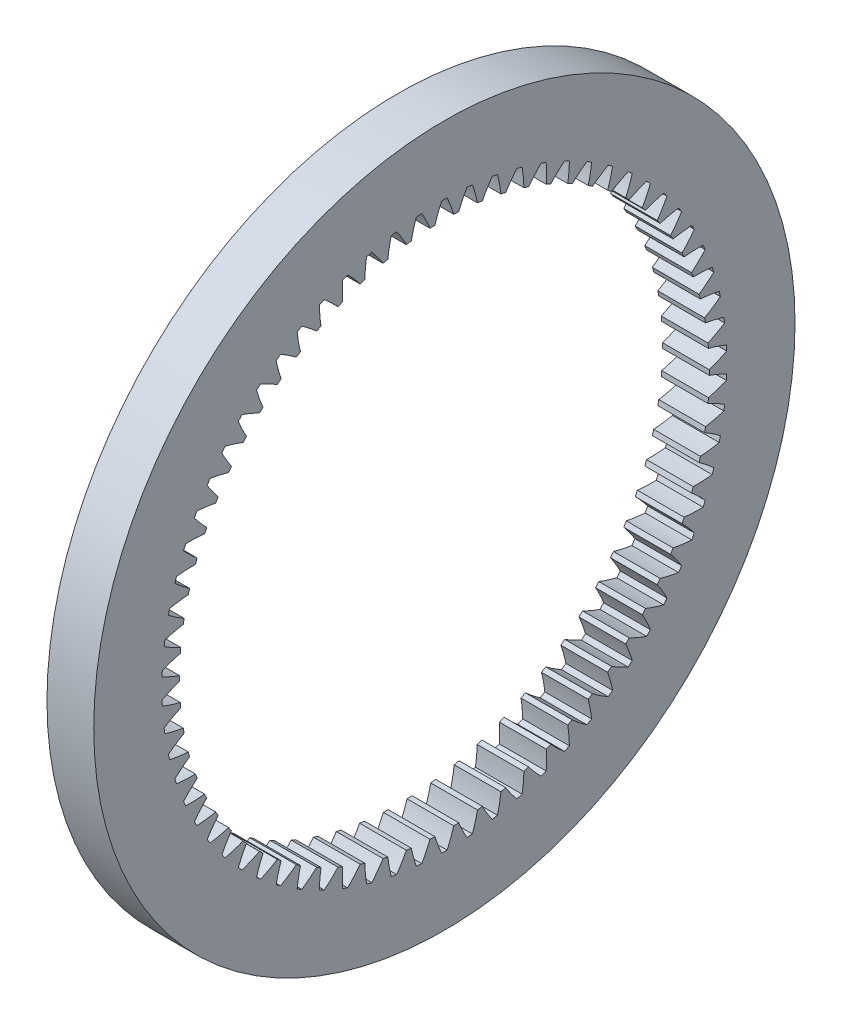
SolidWorks part; units mm, degrees
ref_plane "Plane1" through (0, 0, 0) normal (0, 0, 1) x (1, 0, 0)
ref_plane "Plane2" through (0, 0, 0) normal (0, 1, 0) x (1, 0, 0)
ref_plane "Plane3" through (0, 0, 0) normal (1, 0, 0) x (0, 0, -1)
sketch "HoldingSke" plane through (0, 0, 0) normal (0, 1, 0) x (1, 0, 0)
  line L0 (0, 0) -> (0.0684, -0.1879)
  line L1 (-15, 0) -> (100, 0) construction
  line L2 (0, 0) -> (-2.1039, 2.3779)
  line L3 (0, 0) -> (-11.863, 4.5341)
  line L4 (0, 0) -> (2.9537, 8.1152)
  line L5 (0, 0) -> (-23.7986, -8.8762)
  line L6 (0, 0) -> (-10.5278, -7.1032)
  line L7 (-2.1039, 2.3779) -> (3.3635, 27.1825)
  line L8 (-76.2, 7.3779) -> (-54.61, 7.3779)
  line L9 (-71.009, 38.7566) -> (-53.1078, 45.2721)
  line L10 (-76.2, 71.12) -> (104.1128, 71.12)
  line L11 (0, 0) -> (-30, 0)
  line L12 (-76.2, 101.6) -> (-76.033, 101.6)
  line L13 (24.9733, 27.94) -> (52.9518, 28.4284)
  line L14 (24.9733, 27.94) -> (24.9743, 27.94)
  line L15 (24.9733, 27.94) -> (100.4006, 29.5858)
  circle A0 centre (0, 0) radius 225
  circle A1 centre (0, 0) radius 12.7
  circle A2 centre (0, 0) radius 12.7
  dimension "MHD" = 25.4
  dimension "Hub_dia" = 25.4
  dimension "Diameter" = 450
  dimension "Num_teeth" = 70
  dimension "Pitch" = 0.2
  dimension "Overall_len" = 25.4
  dimension "Show_teeth" = 70
  dimension "Thickness" = 12.7
  dimension "OAL" = 25.4001
  dimension "T_dim" = 21.59
  dimension "Ap" = 20
  dimension "H" = 19.05
  dimension "Pitch_radius" = 180.3128
  dimension "Width" = 30
  dimension "Backlash" = 0.167
  dimension "Addendum_fac" = 1
  dimension "Dedendum_fac" = 1.25
  dimension "Clearance_fac" = 0.25
  dimension "Dedendum_add" = 0.001
  dimension "Module" = 5
sketch "BasProSke" plane through (0, 0, 0) normal (0, 1, 0) x (1, 0, 0)
  line L0 (-10, 0) -> (60, 0) construction
  line L1 (0, 170) -> (0, 225)
  line L2 (0, 170) -> (30, 170)
  line L3 (30, 170) -> (30, 225)
  line L4 (30, 225) -> (0, 225)
  dimension "Diameter" = 450
  dimension "Thickness" = 30
  dimension "Inside_diameter" = 340
revolve "Base-Revolve" add sketch "BasProSke" angle 360 about L0
sketch "TooCutSke" plane through (0, 0, 0) normal (1, 0, 0) x (0, 0, -1)
  line L3 (4.3442, 174.9461) -> (4.3442, 53.6633) construction
  line L4 (0, 0) -> (0, 59.563) construction
  line L5 (0, 0) -> (-3.0655, 68.2587) construction
  line L6 (-77.747, 144.6591) -> (31.1646, 149.5504) construction
  circle A0 centre (0, 0) radius 175 construction
  circle A1 centre (0, 0) radius 181.251 construction
  circle A2 centre (0, 0) radius 148.0016 construction
  circle A3 centre (0, 0) radius 169.9746 construction
  arc A4 (6.0433, 169.8671) -> (1.7382, 181.2427) centre (-77.747, 144.6591) ccw
  arc A5 (6.0433, 169.8671) -> (-6.0433, 169.8671) centre (0, 0) ccw
  arc A6 (1.7382, 181.2427) -> (-1.7382, 181.2427) centre (0, 0) ccw
  arc A7 (-1.7382, 181.2427) -> (-6.0433, 169.8671) centre (77.747, 144.6591) ccw
  dimension "Pitch_dia" = 350
  dimension "Base_dia" = 296.0032
  dimension "Root_dia" = 362.502
  dimension "Overcut_dia" = 339.9492
  dimension "Flank_rad" = 87.5
  dimension "Half_ang" = 2.571
  dimension "Half_CT" = 4.3442
extrude "ToothCut" cut sketch "TooCutSke" along normal through all
fillet "Breaks" [suppressed] radius 0.5
fillet "RootFillets" [suppressed] radius 1.251
pattern_circular "TeethCuts" count 70 every 5.143 about axis through (-10, 0, 0) along (1, 0, 0) of "RootFillets", "Breaks", "ToothCut"
equation "' \"Module@HoldingSke\" = 6.35"
equation "' \"Num_teeth@HoldingSke\" = 24"
equation "' \"Ap@HoldingSke\" =  14.5"
equation "' \"Ap@HoldingSke\" = 14.5"
equation "' \"Width@HoldingSke\" = 12"
equation "' \"Diameter@HoldingSke\" = 8 * 25.4"
equation "' \"Show_teeth@HoldingSke\" = 100"
equation "' \"Backlash@HoldingSke\" = 0.009 * 25.4"
equation "' \"Addendum_fac@HoldingSke\" = 1.0"
equation "' \"Dedendum_fac@HoldingSke\" = 1.25"
equation "' \"Dedendum_add@HoldingSke\" = 0.00005 * 25.4"
equation "' \"Clearance_fac@HoldingSke\" = 0.25"
equation "\"Pitch@HoldingSke\" = 1 / \"Module@HoldingSke\" "
equation "\"Overcut_dia@TooCutSke\" = (\"Num_teeth@HoldingSke\" - 2 * \"Addendum_fac@HoldingSke\") / \"Pitch@HoldingSke\" - 0.002 * 25.4"
equation "\"Pitch_dia@TooCutSke\" = \"Num_teeth@HoldingSke\" / \"Pitch@HoldingSke\""
equation "\"Base_dia@TooCutSke\" = \"Num_teeth@HoldingSke\" / \"Pitch@HoldingSke\" * cos((\"Ap@HoldingSke\"  * 3.14159265 / 180)) * 0.90"
equation "\"Root_dia@TooCutSke\" = \"Num_teeth@HoldingSke\"  / \"Pitch@HoldingSke\" + 2 *  \"Dedendum_fac@HoldingSke\"/ \"Pitch@HoldingSke\" + \"Dedendum_add@HoldingSke\" * 2"
equation "\"Half_ang@TooCutSke\" = 180 / \"Num_teeth@HoldingSke\""
equation "\"Half_CT@TooCutSke\" = \"Num_teeth@HoldingSke\" / \"Pitch@HoldingSke\" * sin((3.14159265 / 2 / \"Num_teeth@HoldingSke\")) / 2 + 10 * \"Backlash@HoldingSke\" / 4"
equation "\"Flank_rad@TooCutSke\" = \"Num_teeth@HoldingSke\" / \"Pitch@HoldingSke\" / 4"
equation "\"Radius@RootFillets\"= \"Clearance_fac@HoldingSke\" / \"Pitch@HoldingSke\" + \"Dedendum_add@HoldingSke\""
equation "\"Break_rad@Breaks\" = 0.02 / \"Pitch@HoldingSke\" * 5"
equation "\"Num_teeth@TeethCuts\" = int( \"Show_teeth@HoldingSke\" ) + 1"
equation "\"Num_teeth@TeethCuts\" = ((sgn( \"Num_teeth@TeethCuts\" - \"Num_teeth@HoldingSke\" )-1)*( \"Num_teeth@TeethCuts\" - \"Num_teeth@HoldingSke\" ))/-2+ \"Num_teeth@HoldingSke\""
equation "\"Num_teeth@TeethCuts\" = ((sgn( \"Num_teeth@TeethCuts\" - 2.0)+1)*( \"Num_teeth@TeethCuts\" - 2.0))/2 +2.0"
equation "\"Angle@TeethCuts\" = 360.0 / \"Num_teeth@HoldingSke\""
equation "\"Diameter@BasProSke\" = \"Num_teeth@HoldingSke\"  / \"Pitch@HoldingSke\" + 2 *  \"Dedendum_fac@HoldingSke\"/ \"Pitch@HoldingSke\" + \"Dedendum_add@HoldingSke\" * 2 + 0.002 * 25.4"
equation "\"Diameter@BasProSke\" = ((sgn( \"Diameter@BasProSke\"  - \"Diameter@HoldingSke\" )+1)*( \"Diameter@BasProSke\"  - \"Diameter@HoldingSke\" ))/2 + \"Diameter@HoldingSke\""
equation "\"Inside_diameter@BasProSke\" =  (\"Num_teeth@HoldingSke\" - 2 * \"Addendum_fac@HoldingSke\") / \"Pitch@HoldingSke\" "
equation "\"Thickness@BasProSke\"  = \"Width@HoldingSke\""
